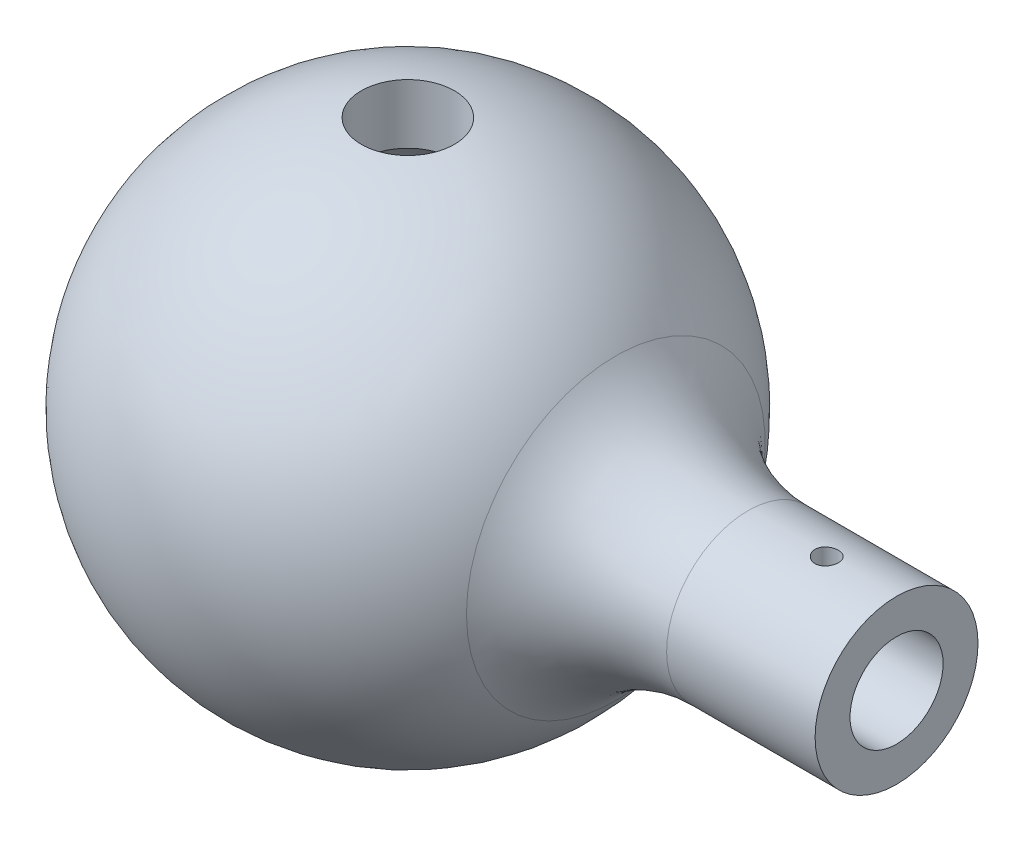
SolidWorks part; units mm, degrees
ref_plane "Plan de face" through (0, 0, 0) normal (0, 0, 1) x (1, 0, 0)
ref_plane "Plan de dessus" through (0, 0, 0) normal (0, 1, 0) x (1, 0, 0)
ref_plane "Plan de droite" through (0, 0, 0) normal (1, 0, 0) x (0, 0, -1)
sketch "Esquisse1" plane through (0, 0, 0) normal (0, 0, 1) x (1, 0, 0)
  line L0 (-11, 0) -> (11, 0)
  arc A0 (11, 0) -> (-11, 0) centre (0, 0) ccw
  dimension "D1" = 22
revolve "Révolution1" add sketch "Esquisse1" angle 360 about L0
shell "Coque1" thickness 2.5
sketch "Esquisse2" plane through (0, 0, 0) normal (0, 1, 0) x (1, 0, 0)
  circle A0 centre (0, 0) radius 2
  dimension "D1" = 4
extrude "Enlèv. mat.-Extru.1" cut sketch "Esquisse2" against normal through all and the other way through all
sketch "Esquisse3" plane through (0, 0, 0) normal (1, 0, 0) x (0, 0, -1)
  circle A0 centre (0, 0) radius 3.5
  dimension "D1" = 7
extrude "Extru.-Mince1" add sketch "Esquisse3" along normal blind 21 thin thin type one direction reverse wall 1.5
fillet "Congé1" radius 7 1 edges at (10.4283, 0, 3.5)
sketch "Esquisse4" plane through (0, 0, 0) normal (0, 0, 1) x (1, 0, 0)
  line L0 (-9.2872, 5.8948) -> (-12.4937, 0.8429)
  line L2 (-9.3076, 0.0324) -> (-9.2872, 5.8948)
  line L3 (-9.3076, 0.0324) -> (-12.7273, 0.0443)
  arc A0 (-2, 10.8167) -> (-2, -10.8167) centre (0, 0) ccw construction
  arc A1 (-12.7273, 0.0443) -> (-12.4937, 0.8429) centre (-11.2273, 0.0391) cw
  dimension "D2" = 1.5
revolve "Révolution4" add sketch "Esquisse4" angle 360 about L3
sketch "Esquisse5" plane through (0, 0, 0) normal (0, 1, 0) x (1, 0, 0)
  line L0 (21, -3.5) -> (21, 3.5) construction
  circle A0 centre (18, 0) radius 0.5
  dimension "D1" = 1
  dimension "D2" = 3
extrude "Enlèv. mat.-Extru.2" cut sketch "Esquisse5" against normal through all and the other way through all
